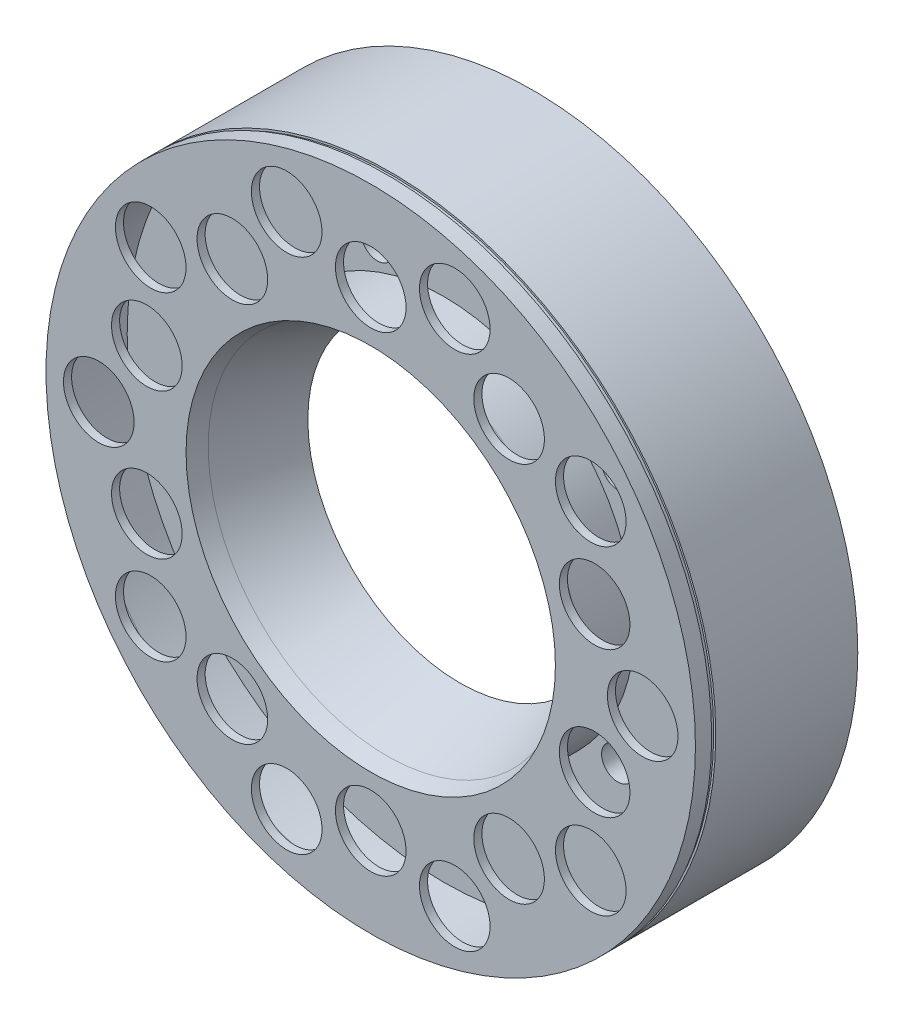
SolidWorks part; units mm, degrees
ref_plane "Front Plane" through (0, 0, 0) normal (0, 0, 1) x (1, 0, 0)
ref_plane "Top Plane" through (0, 0, 0) normal (0, 1, 0) x (1, 0, 0)
ref_plane "Right Plane" through (0, 0, 0) normal (1, 0, 0) x (0, 0, -1)
sketch "Sketch1" plane through (0, 0, 0) normal (0, 0, 1) x (1, 0, 0)
  circle A0 centre (0, 0) radius 101.6
  dimension "D1" = 203.2
extrude "Boss-Extrude2" add sketch "Sketch1" against normal blind 50.8 contours A0
sketch "Sketch5" plane through (0, 0, 0) normal (0, 0, 1) x (1, 0, 0)
  circle A0 centre (0, 0) radius 57.785
  dimension "D1" = 115.57
extrude "Cut-Extrude1" cut sketch "Sketch5" against normal blind 50.8 draft 20 contours A0
sketch "Sketch6" plane through (0, 0, 0) normal (0, 0, 1) x (1, 0, 0)
  circle A1 centre (0, 73.66) radius 11.049
  circle A2 centre (43.2963, 59.5922) radius 11.049
  circle A3 centre (70.0548, 22.7622) radius 11.049
  circle A4 centre (70.0548, -22.7622) radius 11.049
  circle A5 centre (43.2963, -59.5922) radius 11.049
  circle A6 centre (0, -73.66) radius 11.049
  circle A7 centre (-43.2963, -59.5922) radius 11.049
  circle A8 centre (-70.0548, -22.7622) radius 11.049
  circle A9 centre (-70.0548, 22.7622) radius 11.049
  circle A10 centre (-43.2963, 59.5922) radius 11.049
  point P26 (0, 0)
  dimension "D2" = 22.098
  dimension "D3" = 10
extrude "Cut-Extrude2" cut sketch "Sketch6" against normal blind 22.86
sketch "Sketch7" plane through (0, 0, 0) normal (0, 0, 1) x (1, 0, 0)
  circle A2 centre (-85.09, 0) radius 11.049
  circle A3 centre (-68.8393, 50.0146) radius 11.049
  circle A4 centre (-26.2943, 80.9254) radius 11.049
  circle A5 centre (26.2943, 80.9254) radius 11.049
  circle A6 centre (68.8393, 50.0146) radius 11.049
  circle A7 centre (85.09, 0) radius 11.049
  circle A8 centre (68.8393, -50.0146) radius 11.049
  circle A9 centre (26.2943, -80.9254) radius 11.049
  circle A10 centre (-26.2943, -80.9254) radius 11.049
  circle A11 centre (-68.8393, -50.0146) radius 11.049
  point P26 (0, 0)
  dimension "D1" = 10
  dimension "D2" = 22.098
extrude "Cut-Extrude3" cut sketch "Sketch7" against normal blind 22.86
sketch "Sketch8" plane through (0, 0, -50.8) normal (0, 0, -1) x (-1, 0, 0)
  circle A0 centre (0, 0) radius 99.06
  dimension "D1" = 198.12
extrude "Cut-Extrude4" cut sketch "Sketch8" against normal blind 22.86
ref_plane "Plane1" through (0, 0, -22.86) normal (0, 0, 1) x (1, 0, 0)
sketch "Sketch11" plane through (0, 0, -22.86) normal (0, 0, 1) x (1, 0, 0)
  circle A0 centre (0, 0) radius 99.06
  circle A1 centre (0, 0) radius 59.69
  dimension "D1" = 198.12
  dimension "D2" = 119.38
extrude "Cut-Extrude6" cut sketch "Sketch11" along normal blind 20.32
sketch "Sketch12" plane through (0, 0, -22.86) normal (0, 0, 1) x (1, 0, 0)
  circle A2 centre (-67.31, 0) radius 5.08
  circle A4 centre (-20.7999, 64.0156) radius 5.08
  circle A6 centre (54.4549, 39.5638) radius 5.08
  circle A8 centre (54.4549, -39.5638) radius 5.08
  circle A10 centre (-20.7999, -64.0156) radius 5.08
  point P21 (0, 0)
  dimension "D2" = 10.16
  dimension "D3" = 5
extrude "Cut-Extrude7" cut sketch "Sketch12" against normal blind 5.08
ref_plane "Plane2" through (0, 0, -5.08) normal (0, 0, 1) x (1, 0, 0)
split "Split1" trim tools "Plane2" bodies to split 109 resulting bodies 110 111
sketch "Sketch14" plane through (0, 0, -50.8) normal (0, 0, -1) x (-1, 0, 0)
  circle A0 centre (0, 0) radius 100.453
extrude "Cut-Extrude8" cut sketch "Sketch14" against normal blind 2.54
sketch "Sketch17" plane through (0, 0, -5.08) normal (0, 0, 1) x (1, 0, 0)
  circle A0 centre (0, 0) radius 100.965
  dimension "D1" = 201.93
sketch "Sketch19" plane through (0, 0, 0) normal (0, 0, 1) x (1, 0, 0)
  circle A0 centre (0, 0) radius 101.6
  circle A1 centre (0, 0) radius 100.965
  dimension "D1" = 203.2
  dimension "D2" = 201.93
sketch "Sketch20" plane through (0, 0, -5.08) normal (0, 0, 1) x (1, 0, 0)
  circle A0 centre (0, 0) radius 101.6
  circle A1 centre (0, 0) radius 100.965
  dimension "D1" = 201.93
  dimension "D2" = 203.2
extrude "Cut-Extrude12" cut sketch "Sketch20" against normal blind 1.27
sketch "Sketch21" plane through (0, 0, -5.08) normal (0, 0, 1) x (1, 0, 0)
  circle A0 centre (0, 0) radius 100.33
  circle A1 centre (0, 0) radius 100.965
  dimension "D1" = 201.93
  dimension "D2" = 200.66
extrude "Cut-Extrude13" cut sketch "Sketch21" along normal blind 1.27
sketch "Sketch22" plane through (0, 0, -5.08) normal (0, 0, 1) x (1, 0, 0)
  circle A0 centre (0, 0) radius 57.785
  circle A1 centre (0, 0) radius 58.42
  dimension "D1" = 115.57
  dimension "D2" = 116.84
extrude "Cut-Extrude14" cut sketch "Sketch22" against normal blind 1.27
sketch "Sketch23" plane through (0, 0, -5.08) normal (0, 0, 1) x (1, 0, 0)
  circle A0 centre (0, 0) radius 58.42
  circle A1 centre (0, 0) radius 59.055
  dimension "D1" = 116.84
  dimension "D2" = 118.11
sketch "Sketch24" plane through (0, 0, -5.08) normal (0, 0, 1) x (1, 0, 0)
  circle A0 centre (0, 0) radius 58.42
  circle A1 centre (0, 0) radius 59.055
  dimension "D1" = 116.84
  dimension "D2" = 118.11
extrude "Cut-Extrude16" cut sketch "Sketch24" along normal blind 1.27
equation "\"0.05n\"=0.1"
